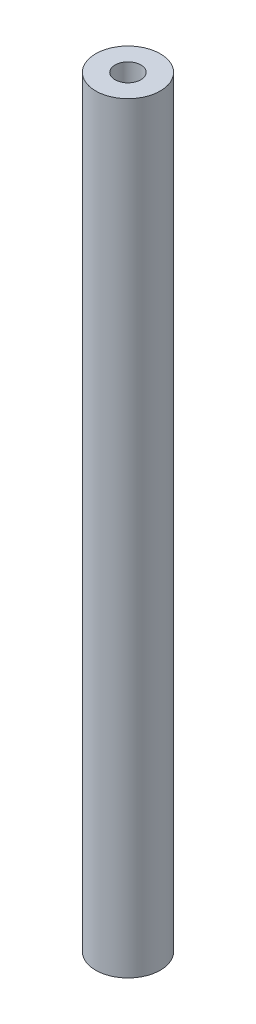
SolidWorks part; units mm, degrees
material "Rubber"
ref_plane "Front Plane" through (0, 0, 0) normal (0, 0, 1) x (1, 0, 0)
ref_plane "Top Plane" through (0, 0, 0) normal (0, 1, 0) x (1, 0, 0)
ref_plane "Right Plane" through (0, 0, 0) normal (1, 0, 0) x (0, 0, -1)
sketch "Sketch1" plane through (0, 0, 0) normal (0, 1, 0) x (1, 0, 0)
  circle A1 centre (0, 0) radius 10
  circle A2 centre (0, 0) radius 4
  dimension "D1" = 8
  dimension "D2" = 20
extrude "Boss-Extrude1" add sketch "Sketch1" along normal blind 236
